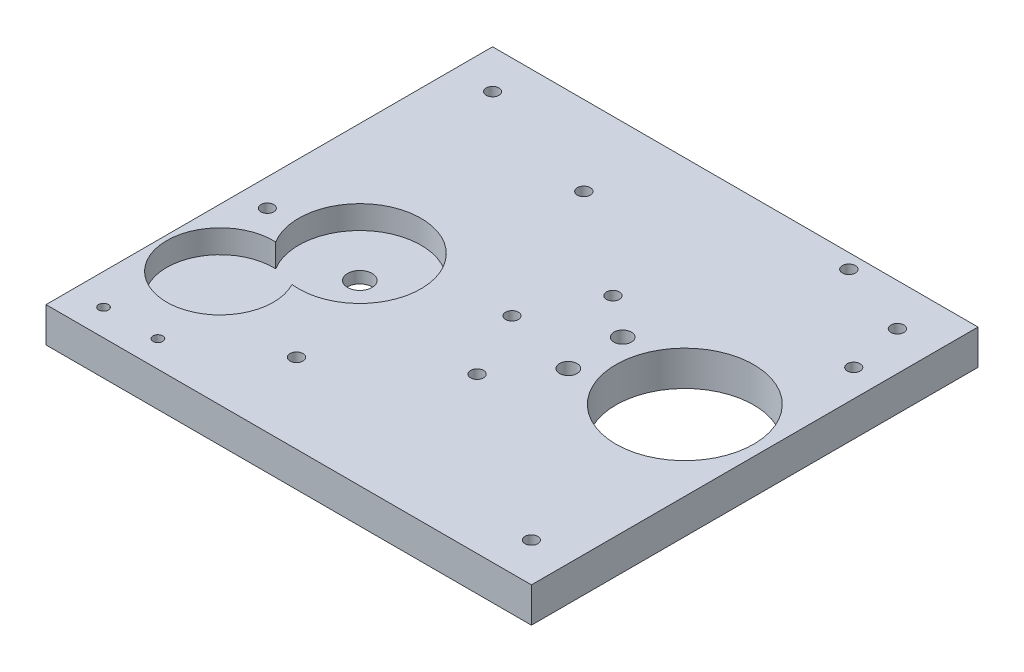
SolidWorks part; units mm, degrees
ref_plane "Front" through (0, 0, 0) normal (0, 0, 1) x (1, 0, 0)
ref_plane "Top" through (0, 0, 0) normal (0, 1, 0) x (1, 0, 0)
ref_plane "Right" through (0, 0, 0) normal (1, 0, 0) x (0, 0, -1)
sketch "Sketch1" plane through (0, 0, 0) normal (0, 1, 0) x (1, 0, 0)
  line L1 (0, 0) -> (125, 0)
  line L2 (0, 0) -> (0, 115)
  line L3 (0, 115) -> (125, 115)
  line L4 (125, 0) -> (125, 115)
  dimension "D1" = 125
  dimension "D2" = 115
extrude "Top_Base" add sketch "Sketch1" along normal blind 9
sketch "Fingers_Position" plane through (0, 9, 0) normal (0, 1, 0) x (1, 0, 0)
  line L0 (74.5, 94.5) -> (39.5, 94.5) construction
  line L1 (74.5, 78.5) -> (19.5, 78.5) construction
  line L2 (74.5, 78.5) -> (74.5, 110.5) construction
  line L3 (74.5, 110.5) -> (19.5, 110.5) construction
  line L4 (19.5, 78.5) -> (19.5, 110.5) construction
  line L5 (74.5, 9.5) -> (19.5, 9.5) construction
  line L6 (74.5, 9.5) -> (74.5, 41.5) construction
  line L7 (74.5, 41.5) -> (19.5, 41.5) construction
  line L8 (19.5, 9.5) -> (19.5, 41.5) construction
  line L10 (39.5, 25.5) -> (74.5, 25.5) construction
  line L11 (125, 115) -> (0, 115) construction
  line L12 (0, 115) -> (0, 0) construction
  dimension "D1" = 55
  dimension "D2" = 32
  dimension "D3" = 69
  dimension "D4" = 4.5
  dimension "D5" = 19.5
  dimension "D6" = 20
sketch "Intermediate_Gear_Position" plane through (0, 9, 0) normal (0, 1, 0) x (1, 0, 0)
  line L0 (0, 51.7935) -> (29.0154, 51.7935) construction
  line L1 (0, 115) -> (0, 0) construction
  line L2 (29.0154, 51.7935) -> (29.0154, 115) construction
  line L3 (125, 115) -> (0, 115) construction
  line L4 (29.0154, 51.7935) -> (29.0154, 0) construction
  line L5 (0, 0) -> (125, 0) construction
  circle A0 centre (29.0154, 51.7935) radius 15.5 construction
  circle A1 centre (29.0154, 51.7935) radius 13.5625
  circle A2 centre (29.0154, 51.7935) radius 13.8125 construction
  dimension "D3" = 31
  dimension "D4" = 27.125
  dimension "D5" = 27.625
  dimension "D1" = 29.0154
  dimension "D2" = 51.7935
sketch "Drive_Gear_Position" plane through (0, 9, 0) normal (0, 1, 0) x (1, 0, 0)
  line L0 (3, 20.8203) -> (27, 20.8203) construction
  line L1 (3, 38.8203) -> (27, 38.8203)
  line L2 (3, 38.8203) -> (3, 2.8203)
  line L3 (3, 2.8203) -> (27, 2.8203)
  line L4 (27, 38.8203) -> (27, 2.8203)
  line L5 (15, 38.8203) -> (15, 2.8203) construction
  line L6 (95.5, 103) -> (95.5, 48) construction
  line L7 (79.5, 103) -> (111.5, 103) construction
  line L8 (79.5, 103) -> (79.5, 48) construction
  line L9 (79.5, 48) -> (111.5, 48) construction
  line L10 (111.5, 103) -> (111.5, 48) construction
  line L11 (77.5, 72) -> (113.5, 72) construction
  line L12 (77.5, 72) -> (77.5, 48) construction
  line L13 (77.5, 48) -> (113.5, 48) construction
  line L14 (113.5, 72) -> (113.5, 48) construction
  line L15 (95.5, 72) -> (95.5, 48) construction
  line L17 (125, 0) -> (125, 115) construction
  line L18 (125, 115) -> (0, 115) construction
  line L20 (0, 115) -> (0, 0) construction
  circle A0 centre (15, 29.8203) radius 9 construction
  circle A1 centre (15, 29.8203) radius 13.5 construction
  circle A2 centre (15, 29.8203) radius 12
  circle A4 centre (15, 29.8203) radius 12.25 construction
  circle A5 centre (29.0154, 51.7935) radius 13.8125 construction
  dimension "D1" = 27
  dimension "D2" = 18
  dimension "D5" = 24
  dimension "D13" = 24.5
  dimension "D3" = 24
  dimension "D4" = 36
  dimension "D6" = 32
  dimension "D7" = 55
  dimension "D8" = 24
  dimension "D9" = 36
  dimension "D10" = 13.5
  dimension "D11" = 12
  dimension "D12" = 3
sketch "Sketch5" plane through (0, 9, 0) normal (0, 1, 0) x (1, 0, 0)
  circle A0 centre (29.0154, 51.7935) radius 15.75
  circle A1 centre (15, 29.8203) radius 13.75
  dimension "D1" = 27.5
  dimension "D2" = 31.5
extrude "Gears_Extrude_Cut" cut sketch "Sketch5" against normal blind 6 contours A0 A1 | A1 A0 | A0 A1
sketch "Sketch7" plane through (0, 9, 0) normal (0, 1, 0) x (1, 0, 0)
  circle A0 centre (29.0154, 51.7935) radius 3.15
  dimension "D1" = 6.3
extrude "Key_Extrude_Cut" cut sketch "Sketch7" against normal through all
sketch "Sketch8" plane through (0, 9, 0) normal (0, 1, 0) x (1, 0, 0)
  line L0 (113.5, 60) -> (77.5, 60) construction
  line L1 (113.5, 72) -> (113.5, 48) construction
  line L2 (77.5, 72) -> (77.5, 48) construction
  circle A0 centre (104.5, 60) radius 9 construction
  circle A1 centre (104.5, 60) radius 17.75
  dimension "D1" = 18
  dimension "D2" = 35.5
extrude "Thumb_Extrude_Cut" cut sketch "Sketch8" against normal through all
sketch "Sketch9" plane through (0, 9, 0) normal (0, 1, 0) x (1, 0, 0)
  line L0 (74.5, 78.5) -> (19.5, 78.5) construction
  line L1 (74.5, 71.5) -> (67.5, 71.5) construction
  line L2 (74.5, 71.5) -> (74.5, 78.5) construction
  line L3 (74.5, 78.5) -> (67.5, 78.5) construction
  line L4 (67.5, 71.5) -> (67.5, 78.5) construction
  line L5 (74.5, 71.5) -> (67.5, 78.5) construction
  line L6 (74.5, 78.5) -> (67.5, 71.5) construction
  line L11 (125, 57.5) -> (0, 57.5) construction
  line L12 (125, 0) -> (125, 115) construction
  line L14 (74.5, 78.5) -> (74.5, 110.5) construction
  line L16 (0, 115) -> (0, 0) construction
  line L17 (74.5, 110.5) -> (19.5, 110.5) construction
  line L18 (74.5, 78.5) -> (47.5, 78.5) construction
  line L19 (74.5, 78.5) -> (74.5, 110.5) construction
  line L20 (74.5, 110.5) -> (47.5, 110.5) construction
  line L21 (47.5, 78.5) -> (47.5, 110.5) construction
  line L26 (74.5, 94.5) -> (39.5, 94.5) construction
  line L27 (40.5, 98) -> (47.5, 98) construction
  line L28 (40.5, 98) -> (40.5, 91) construction
  line L29 (40.5, 91) -> (47.5, 91) construction
  line L30 (47.5, 98) -> (47.5, 91) construction
  line L31 (40.5, 98) -> (47.5, 91) construction
  line L32 (40.5, 91) -> (47.5, 98) construction
  line L33 (27, 2.8203) -> (27, 0.8203) construction
  line L34 (27, 0.8203) -> (22, 0.8203) construction
  line L35 (22, 0.8203) -> (22, 6.8203) construction
  line L36 (77.5, 60) -> (113.5, 60) construction
  line L37 (77.5, 72) -> (77.5, 48) construction
  line L38 (113.5, 72) -> (113.5, 48) construction
  line L39 (77.5, 72) -> (75.5, 72) construction
  line L40 (75.5, 72) -> (75.5, 67) construction
  line L41 (75.5, 67) -> (81.5, 67) construction
  line L42 (111.5, 103) -> (111.5, 107.75) construction
  line L43 (111.5, 107.75) -> (95.5, 107.75) construction
  line L44 (111.5, 107.75) -> (115, 107.75) construction
  line L45 (115, 107.75) -> (115, 104.25) construction
  line L46 (95.5, 107.75) -> (95.5, 111.25) construction
  line L47 (15, 2.8203) -> (15, 38.8203) construction
  circle A0 centre (71, 75) radius 1.675
  circle A2 centre (44, 94.5) radius 1.675
  circle A3 centre (22, 6.8203) radius 2.25 construction
  circle A4 centre (81.5, 67) radius 2.25
  circle A5 centre (95.5, 111.25) radius 1.675
  circle A6 centre (115, 104.25) radius 1.675
  circle A7 centre (71, 40) radius 1.675
  circle A8 centre (44, 20.5) radius 1.675
  circle A9 centre (8, 6.8203) radius 2.25 construction
  circle A10 centre (81.5, 53) radius 2.25
  point P0 (71, 75)
  point P18 (44, 94.5)
  dimension "D3" = 3.35
  dimension "D10" = 4.5
  dimension "D14" = 4.5
  dimension "D1" = 7
  dimension "D2" = 7
  dimension "D4" = 27
  dimension "D5" = 7
  dimension "D6" = 7
  dimension "D7" = 2
  dimension "D8" = 5
  dimension "D9" = 6
  dimension "D11" = 2
  dimension "D12" = 5
  dimension "D13" = 6
  dimension "D15" = 4.75
  dimension "D16" = 16
  dimension "D17" = 3.5
  dimension "D18" = 3.5
  dimension "D19" = 3.5
extrude "Mount_Holes" cut sketch "Sketch9" against normal blind 5
sketch "Sketch11" plane through (0, 9, 0) normal (0, 1, 0) x (1, 0, 0)
  line L0 (0, 115) -> (10, 115) construction
  line L1 (125, 115) -> (0, 115) construction
  line L2 (10, 115) -> (10, 105) construction
  line L3 (125, 0) -> (115, 0) construction
  line L4 (0, 0) -> (125, 0) construction
  line L5 (115, 0) -> (115, 10) construction
  line L6 (0, 57.5) -> (125, 57.5) construction
  line L7 (0, 115) -> (0, 0) construction
  line L8 (125, 0) -> (125, 115) construction
  line L9 (62.5, 115) -> (62.5, 0) construction
  line L10 (125, 115) -> (125, 90) construction
  line L11 (125, 90) -> (118, 90) construction
  line L12 (0, 0) -> (0, 50) construction
  line L13 (0, 50) -> (7, 50) construction
  circle A0 centre (10, 105) radius 2.8
  circle A1 centre (115, 10) radius 2.8
  circle A2 centre (62.5, 57.5) radius 2.8
  circle A3 centre (118, 90) radius 2.8
  circle A4 centre (7, 50) radius 2.8
  dimension "D5" = 5.6
  dimension "D1" = 10
  dimension "D2" = 10
  dimension "D3" = 10
  dimension "D4" = 10
  dimension "D6" = 25
  dimension "D7" = 7
  dimension "D8" = 50
  dimension "D9" = 7
hole_wizard "M3x0.5 Tapped Hole1" positions "3DSketch1" profile "Sketch14" tap size "M3x0.5" standard "ANSI Metric"
sketch3d "3DSketch1"
  point P0 (8, 9, -6.8203)
  point P3 (22, 9, -6.8203)
sketch "Sketch14" plane through (8, 9, -6.8203) normal (1, 0, 0) x (0, 0, 1)
  line L0 (0, 0) -> (0, 8.2511)
  line L1 (0, 8.2511) -> (1.25, 7.5)
  line L2 (1.25, 7.5) -> (1.25, 0)
  line L5 (1.25, 0) -> (0, 0)
  line L10 (0, 8.2511) -> (-1.25, 7.5) construction
  line L11 (0, -6.35) -> (0, 107.95) construction
  dimension "Tap Drill Dia." = 2.5
  dimension "Tap Drill Depth" = 7.5
  dimension "Drill Angle" = 118
cosmetic thread "Hole Thread1" parameters "D1"=6, "D2"=3
cosmetic thread "Hole Thread2" parameters "D1"=6, "D2"=3
hole_wizard "M4x0.7 Tapped Hole1" positions "3DSketch3" profile "Sketch16" tap size "M4x0.7" standard "ANSI Metric"
sketch3d "3DSketch3"
  point P0 (10, 9, -105)
  point P3 (118, 9, -90)
  point P6 (115, 9, -10)
  point P9 (7, 9, -50)
  point P12 (62.5, 9, -57.5)
sketch "Sketch16" plane through (10, 9, -105) normal (1, 0, 0) x (0, 0, 1)
  line L0 (0, 0) -> (0, 11.0914)
  line L1 (0, 11.0914) -> (1.65, 10.1)
  line L2 (1.65, 10.1) -> (1.65, 0)
  line L5 (1.65, 0) -> (0, 0)
  line L10 (0, 11.0914) -> (-1.65, 10.1) construction
  line L11 (0, -6.35) -> (0, 107.95) construction
  dimension "Tap Drill Dia." = 3.3
  dimension "Tap Drill Depth" = 10.1
  dimension "Drill Angle" = 118
cosmetic thread "Hole Thread3" parameters "D1"=8, "D2"=4
cosmetic thread "Hole Thread4" parameters "D1"=8, "D2"=4
cosmetic thread "Hole Thread5" parameters "D1"=8, "D2"=4
cosmetic thread "Hole Thread6" parameters "D1"=8, "D2"=4
cosmetic thread "Hole Thread7" parameters "D1"=8, "D2"=4
